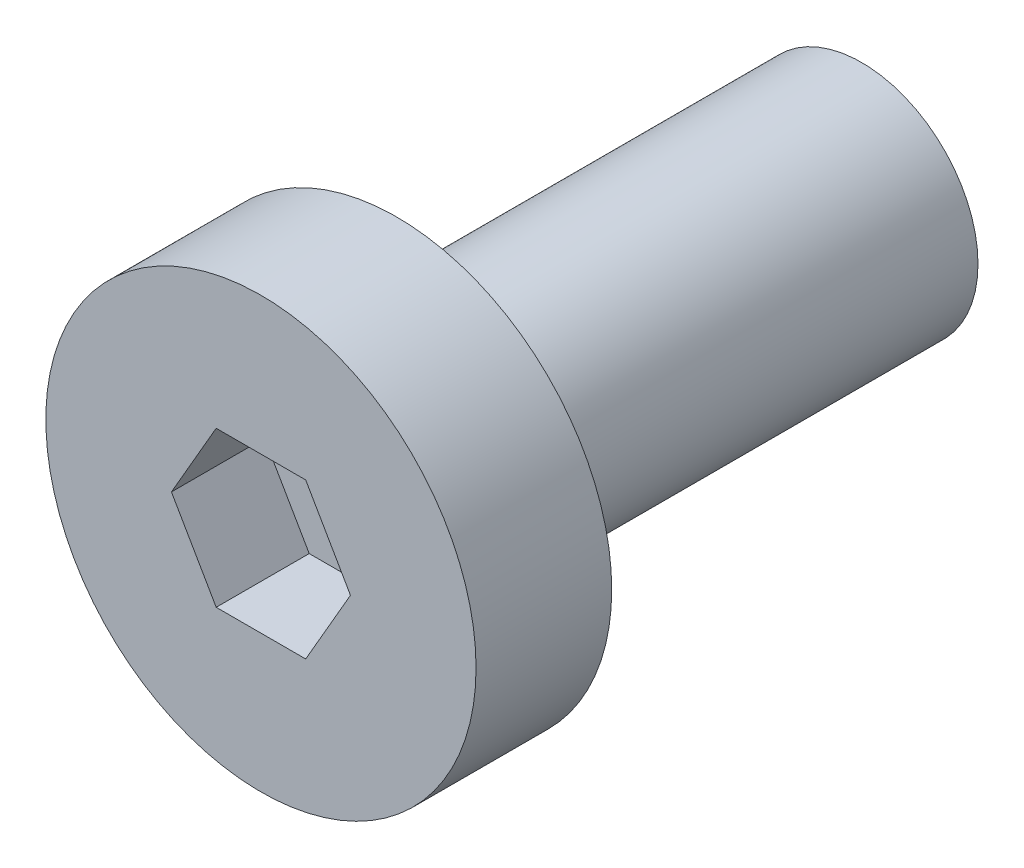
SolidWorks part; units mm, degrees
ref_plane "Front Plane" through (0, 0, 0) normal (0, 0, 1) x (1, 0, 0)
ref_plane "Top Plane" through (0, 0, 0) normal (0, 1, 0) x (1, 0, 0)
ref_plane "Right Plane" through (0, 0, 0) normal (1, 0, 0) x (0, 0, -1)
sketch "Sketch1" plane through (0, 0, 0) normal (0, 0, 1) x (1, 0, 0)
  circle A0 centre (0, 0) radius 2.775
  dimension "D1" = 5.55
extrude "Boss-Extrude1" add sketch "Sketch1" along normal blind 1.75
sketch "Sketch2" plane through (0, 0, 0) normal (0, 0, -1) x (-1, 0, 0)
  circle A0 centre (0, 0) radius 1.5
  dimension "D1" = 3
extrude "Boss-Extrude2" add sketch "Sketch2" along normal blind 6
sketch "Sketch3" plane through (0, 0, 1.75) normal (0, 0, 1) x (1, 0, 0)
  line L1 (1.1547, 0) -> (0.5774, 1)
  line L2 (0.5774, 1) -> (-0.5774, 1)
  line L3 (-0.5774, 1) -> (-1.1547, 0)
  line L4 (-1.1547, 0) -> (-0.5774, -1)
  line L5 (-0.5774, -1) -> (0.5774, -1)
  line L6 (0.5774, -1) -> (1.1547, 0)
  circle A0 centre (0, 0) radius 1 construction
  dimension "D1" = 2
extrude "Cut-Extrude1" cut sketch "Sketch3" against normal blind 1.2
